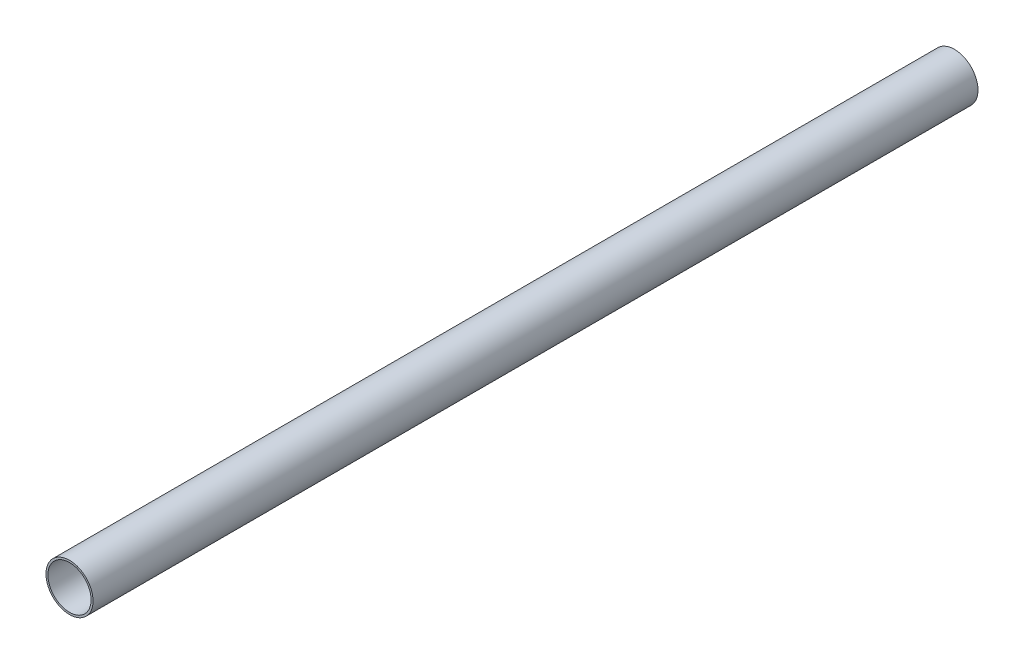
SolidWorks part; units mm, degrees
material "Karbon Fiber Boru "
ref_plane "Ön Düzlem" through (0, 0, 0) normal (0, 0, 1) x (1, 0, 0)
ref_plane "Üst Düzlem" through (0, 0, 0) normal (0, 1, 0) x (1, 0, 0)
ref_plane "Sağ Düzlem" through (0, 0, 0) normal (1, 0, 0) x (0, 0, -1)
sketch "Çizim1" plane through (0, 0, 0) normal (0, 0, 1) x (1, 0, 0)
  circle A0 centre (0, 0) radius 12
  circle A1 centre (0, 0) radius 11
  dimension "D1" = 24
  dimension "D2" = 22
extrude "Yükseklik-Ekstrüzyon1" add sketch "Çizim1" along normal blind 451
